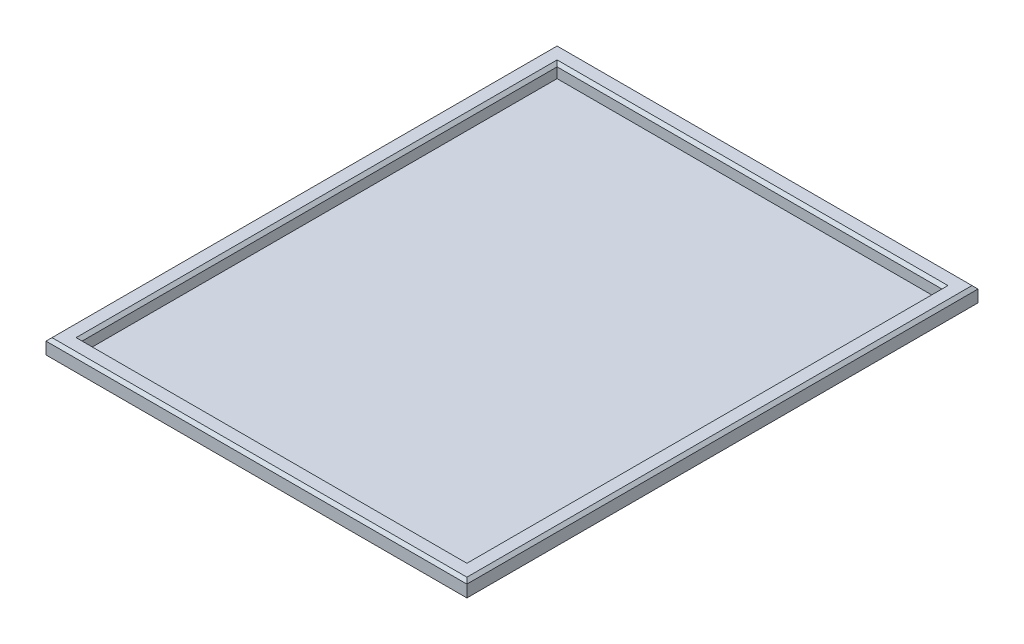
SolidWorks part; units mm, degrees
material "MDF wood"
ref_plane "Front Plane" through (0, 0, 0) normal (0, 0, 1) x (1, 0, 0)
ref_plane "Top Plane" through (0, 0, 0) normal (0, 1, 0) x (1, 0, 0)
ref_plane "Right Plane" through (0, 0, 0) normal (1, 0, 0) x (0, 0, -1)
sketch "Sketch3" plane through (0, 0, 0) normal (0, 1, 0) x (1, 0, 0)
  line L0 (-320, 395) -> (320, 395)
  line L1 (-350, -425) -> (350, -425)
  line L2 (-350, -425) -> (-350, 425)
  line L3 (-350, 425) -> (350, 425)
  line L4 (350, -425) -> (350, 425)
  line L5 (-350, -425) -> (350, 425) construction
  line L6 (-350, 425) -> (350, -425) construction
  line L7 (320, -395) -> (320, 395)
  line L8 (-320, -395) -> (320, -395)
  line L9 (-320, -395) -> (-320, 395)
  point P0 (0, 0)
  dimension "D1" = 700
  dimension "D2" = 850
  dimension "D3" = 30
extrude "Boss-Extrude1" add sketch "Sketch3" along normal blind 30
chamfer "Chamfer2" distance 5 angle 45 12 edges at (0, 0, -425) (-350, 0, 0) (0, 0, 425) (350, 0, 0) (0, 30, 395) (320, 30, 0) (0, 30, -395) (-320, 30, 0) (0, 30, 425) (-350, 30, 0) (0, 30, -425) (350, 30, 0)
sketch "Sketch4" plane through (0, 0, 0) normal (0, -1, 0) x (1, 0, 0)
  line L0 (320, 395) -> (320, -395) construction
  line L1 (320, -395) -> (-320, -395) construction
  line L2 (-320, -395) -> (-320, 395) construction
  line L3 (-320, 395) -> (320, 395) construction
  line L12 (320, 395) -> (320, -395)
  line L13 (320, -395) -> (-320, -395)
  line L14 (-320, -395) -> (-320, 395)
  line L15 (-320, 395) -> (320, 395)
extrude "Boss-Extrude2" add sketch "Sketch4" against normal blind 8 separate body
